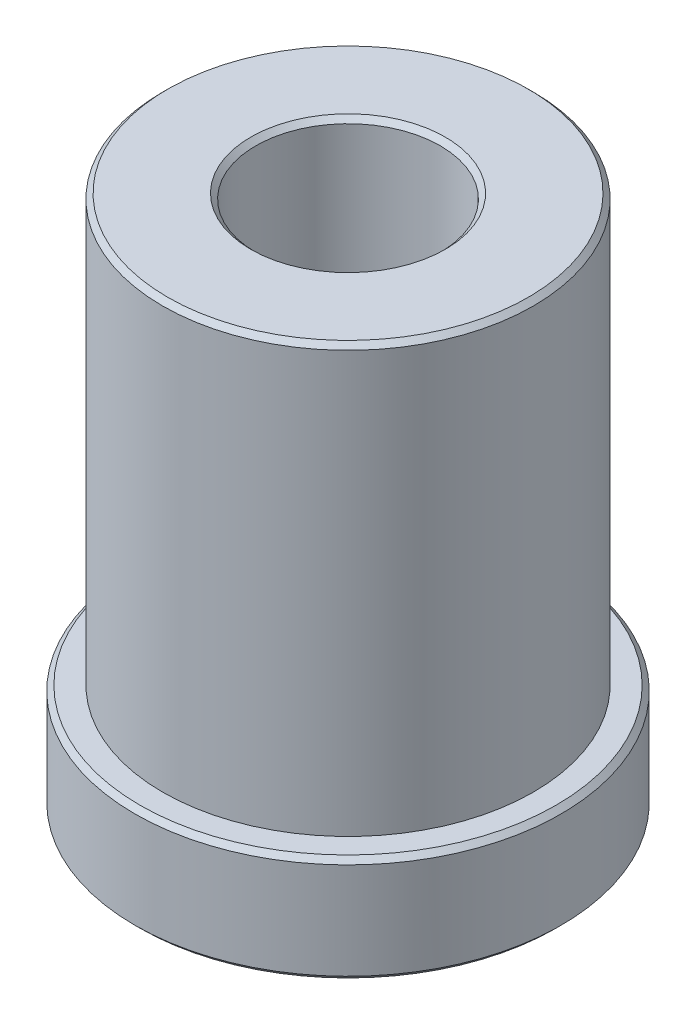
SolidWorks part; units mm, degrees
material "Nylon 101"
ref_plane "Front Plane" through (0, 0, 0) normal (0, 0, 1) x (1, 0, 0)
ref_plane "Top Plane" through (0, 0, 0) normal (0, 1, 0) x (1, 0, 0)
ref_plane "Right Plane" through (0, 0, 0) normal (1, 0, 0) x (0, 0, -1)
sketch "Sketch1" plane through (0, 0, 0) normal (0, 1, 0) x (1, 0, 0)
  circle A0 centre (0, 0) radius 11.049
  dimension "D1" = 22.098
extrude "Boss-Extrude1" add sketch "Sketch1" along normal blind 25.4
sketch "Sketch2" plane through (0, 0, 0) normal (0, -1, 0) x (1, 0, 0)
  circle A0 centre (0, 0) radius 12.7
  dimension "D1" = 25.4
extrude "Boss-Extrude2" add sketch "Sketch2" along normal blind 6.35
sketch "Sketch5" plane through (0, -6.35, 0) normal (0, -1, 0) x (1, 0, 0)
  circle A0 centre (0, 0) radius 11.176
  dimension "D1" = 22.352
extrude "Cut-Extrude2" cut sketch "Sketch5" against normal blind 5.5453
sketch "Sketch6" plane through (0, -0.8047, 0) normal (0, -1, 0) x (1, 0, 0)
  circle A0 centre (0, 0) radius 7.2746
  dimension "D1" = 14.5491
extrude "Cut-Extrude3" cut sketch "Sketch6" against normal blind 0.2
ref_plane "Plane2" through (0, 9.525, 0) normal (0, -1, 0) x (-1, 0, 0)
sketch "Sketch3" plane through (0, -6.35, 0) normal (0, -1, 0) x (1, 0, 0)
  circle A0 centre (0, 0) radius 5.5
  dimension "D1" = 11
extrude "Cut-Extrude1" cut sketch "Sketch3" against normal through all
sketch "Sketch4" plane through (0, -6.35, 0) normal (0, -1, 0) x (1, 0, 0)
  circle A0 centre (0, 0) radius 11.1125
  dimension "D1" = 22.225
chamfer "Chamfer1" distance 0.3 angle 45 6 edges at (0, 0, -12.7) (0, -6.35, -12.7) (0, 25.4, 11.049) (0, 25.4, -5.5) (0, -0.6047, -5.5) (0, -6.35, -11.176)
equation "\"D1@Chamfer1\"=.3mm"
